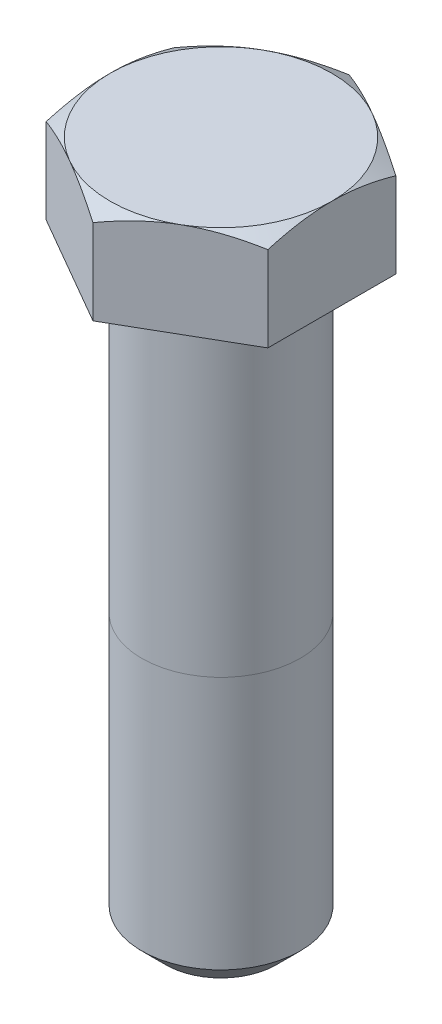
SolidWorks part; units mm, degrees
ref_plane "Front Plane" through (0, 0, 0) normal (0, 0, 1) x (1, 0, 0)
ref_plane "Top Plane" through (0, 0, 0) normal (0, 1, 0) x (1, 0, 0)
ref_plane "Right Plane" through (0, 0, 0) normal (1, 0, 0) x (0, 0, -1)
sketch "Sketch1" plane through (0, 0, 0) normal (0, 1, 0) x (1, 0, 0)
  line L7 (0, -16.1658) -> (14, -8.0829)
  line L8 (14, -8.0829) -> (14, 8.0829)
  line L9 (14, 8.0829) -> (0, 16.1658)
  line L10 (0, 16.1658) -> (-14, 8.0829)
  line L11 (-14, 8.0829) -> (-14, -8.0829)
  line L12 (-14, -8.0829) -> (0, -16.1658)
  circle A0 centre (0, 0) radius 14 construction
  dimension "D1" = 28
extrude "Boss-Extrude1" add sketch "Sketch1" along normal blind 12
sketch "Sketch2" plane through (0, 12, 0) normal (0, 1, 0) x (1, 0, 0)
  line L0 (0, 16.1658) -> (-14, 8.0829) construction
  circle A0 centre (0, 0) radius 14
extrude "Cut-Extrude1" cut sketch "Sketch2" against normal through all draft 60 flip side to cut
sketch "Sketch3" plane through (0, 0, 0) normal (0, -1, 0) x (1, 0, 0)
  circle A0 centre (0, 0) radius 10
  dimension "D1" = 20
extrude "Boss-Extrude2" add sketch "Sketch3" along normal blind 75
chamfer "Chamfer1" distance 3 angle 45 1 edges at (0, -75, -10)
sketch "Sketch4" plane through (0, 0, 0) normal (0, 0, 1) x (1, 0, 0)
  line L0 (-10, -40) -> (10, -40)
  line L1 (-10, 0) -> (-10, -72) construction
  line L2 (10, -72) -> (10, 0) construction
  line L3 (-10, 0) -> (10, 0) construction
  dimension "D1" = 40
split line "Split Line1"
